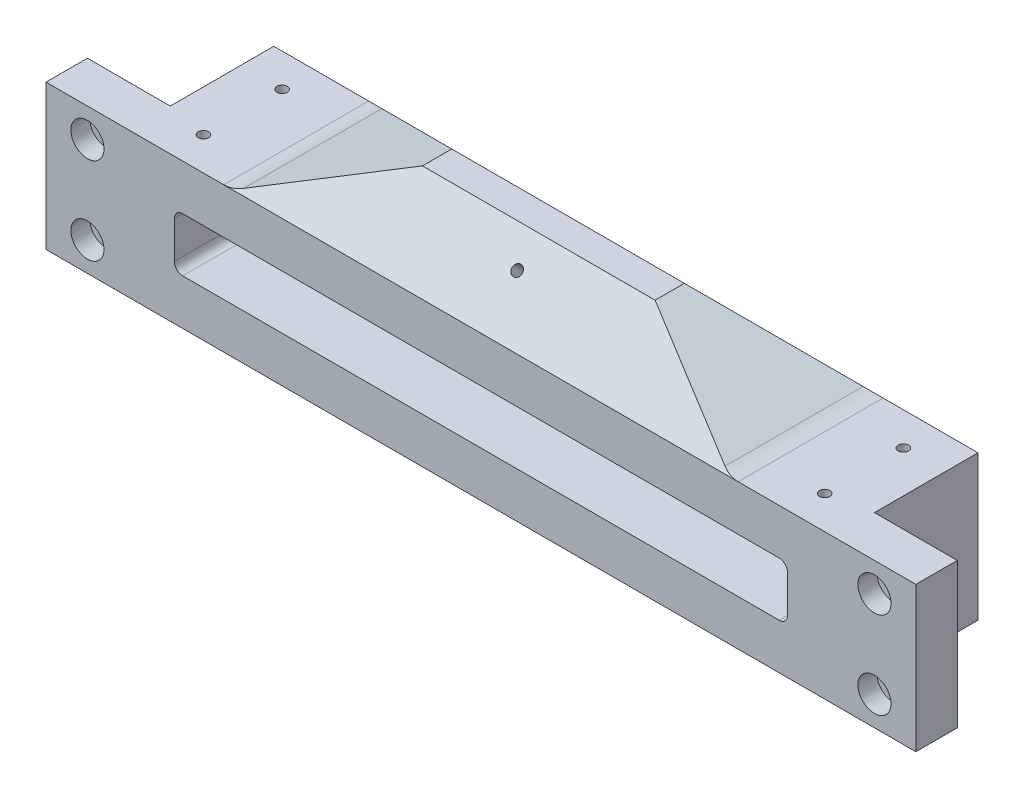
SolidWorks part; units mm, degrees
material "AISI Type 316L stainless steel"
ref_plane "Front Plane" through (0, 0, 0) normal (0, 0, 1) x (1, 0, 0)
ref_plane "Top Plane" through (0, 0, 0) normal (0, 1, 0) x (1, 0, 0)
ref_plane "Right Plane" through (0, 0, 0) normal (1, 0, 0) x (0, 0, -1)
sketch "Sketch1" plane through (0, 0, 0) normal (0, 0, 1) x (1, 0, 0)
  line L1 (80, -12.5) -> (-80, -12.5)
  line L2 (80, -12.5) -> (80, 12.5)
  line L3 (80, 12.5) -> (-80, 12.5)
  line L4 (-80, -12.5) -> (-80, 12.5)
  line L5 (80, -12.5) -> (-80, 12.5) construction
  line L6 (80, 12.5) -> (-80, -12.5) construction
  dimension "D1" = 25
  dimension "D2" = 160
sketch "Sketch2" plane through (0, 0, 0) normal (1, 0, 0) x (0, 0, -1)
  line L0 (17.5, 0) -> (-8.75, 26.25)
  line L1 (0, -12.5) -> (0, 12.5) construction
  line L2 (-17.5, 17.5) -> (0, 35)
  line L3 (0, 12.5) -> (0, -12.5) construction
  line L4 (19.25, 0) -> (-19.25, 0) construction
  line L5 (0, 28.875) -> (0, -28.875) construction
  line L6 (17.5, 17.5) -> (0, 35)
  line L7 (-17.5, 17.5) -> (-17.5, -17.5)
  line L8 (-17.5, -17.5) -> (17.5, -17.5)
  line L9 (17.5, -17.5) -> (17.5, 17.5)
  point P13 (0, 12.5)
  point P19 (0, -12.5)
  dimension "D1" = 45
  dimension "D2" = 5
  dimension "D3" = 5
sketch "Sketch3" plane through (0, 0, 0) normal (0, 0, 1) x (1, 0, 0)
  line L0 (80, -12.5) -> (-80, 12.5) construction
  line L1 (85, -17.5) -> (-85, -17.5)
  line L2 (85, -17.5) -> (85, 17.5)
  line L3 (85, 17.5) -> (-85, 17.5)
  line L4 (-85, -17.5) -> (-85, 17.5)
  line L5 (85, -17.5) -> (-85, 17.5) construction
  line L6 (85, 17.5) -> (-85, -17.5) construction
  line L7 (80, -12.5) -> (-80, -12.5) construction
  line L8 (-80, -12.5) -> (-80, 12.5) construction
  point P0 (0, 0)
  dimension "D1" = 5
  dimension "D2" = 5
extrude "Boss-Extrude1" add sketch "Sketch2" along normal up to vertex (85 mm away) from vertex at -85 contours L8 L9 L0 L2 L7 | L0 L9 L6 L2 starting at point (-85, -17.5, 0)
extrude "Cut-Extrude2" cut sketch "Sketch1" along normal blind 3 from surface at -17.5 starting at face at (0, 0, -17.5)
sketch "Sketch7" plane through (0, 0, -14.5) normal (0, 0, -1) x (-1, 0, 0)
  line L0 (-80, -12.5) -> (-80, 12.5) construction
  line L1 (74, -6.5) -> (-74, -6.5)
  line L2 (74, -6.5) -> (74, 6.5)
  line L3 (74, 6.5) -> (-74, 6.5)
  line L4 (-74, -6.5) -> (-74, 6.5)
  line L5 (74, -6.5) -> (-74, 6.5) construction
  line L6 (74, 6.5) -> (-74, -6.5) construction
  line L7 (-80, 12.5) -> (80, 12.5) construction
  point P0 (0, 0)
  dimension "D1" = 6
  dimension "D2" = 6
extrude "Cut-Extrude4" cut sketch "Sketch7" against normal through all both
sketch "Sketch8" plane through (0, 0, -14.5) normal (0, 0, -1) x (-1, 0, 0)
  line L0 (-74, 6.5) -> (-80, 12.5) construction
  line L1 (77, -9.5) -> (-77, -9.5)
  line L2 (77, -9.5) -> (77, 9.5)
  line L3 (77, 9.5) -> (-77, 9.5)
  line L4 (-77, -9.5) -> (-77, 9.5)
  line L5 (77, -9.5) -> (-77, 9.5) construction
  line L6 (77, 9.5) -> (-77, -9.5) construction
  line L7 (-77, 9.5) -> (0, 9.5)
  point P0 (0, 0)
  point P10 (-38.5, 9.5)
  point P11 (0, 9.5)
  point P12 (-77, 9.5)
sketch "Sketch15" plane through (0, 17.5, 17.5) normal (0, -0.7071, -0.7071) x (1, 0, 0)
  line L0 (-85, 0) -> (85, -24.7487) construction
  line L1 (85, -24.7487) -> (-85, -24.7487) construction
  point P0 (0, -12.3744)
sketch "Sketch5" plane through (0, 0, -17.5) normal (0, 0, -1) x (-1, 0, 0)
  line L0 (-85, 17.5) -> (-60, 17.5)
  line L1 (-85, 17.5) -> (85, 17.5) construction
  line L2 (-60, 17.5) -> (-20, 35)
  line L3 (-85, 35) -> (85, 35) construction
  line L4 (-20, 35) -> (-85, 35)
  line L5 (-85, 35) -> (-85, 17.5)
  dimension "D1" = 25
  dimension "D2" = 65
extrude "Cut-Extrude3" cut sketch "Sketch5" against normal through all both
mirror "Mirror1" about plane through (0, 0, 0) normal (1, 0, 0) of "Cut-Extrude3"
fillet "Fillet1" radius 3 4 edges at (80, 12.5, -16) (80, -12.5, -16) (-80, -12.5, -16) (-80, 12.5, -16)
fillet "Fillet2" radius 10 2 edges at (-60, 17.5, 0) (60, 17.5, 0)
hole_wizard "Tap Drill for M2 Tap1" positions "Sketch9" profile "Sketch11" hole size "M2" standard "GB"
sketch "Sketch9" plane through (0, 0, -14.5) normal (0, 0, -1) x (-1, 0, 0)
  line L0 (-77, -9.5) -> (-77, 9.5) construction
  point P0 (-77, 9.5)
  point P3 (-38.5, 9.5)
  point P6 (0, 9.5)
  point P9 (-77, 0)
sketch "Sketch11" plane through (77, 9.5, -14.5) normal (1, 0, 0) x (0, 1, 0)
  line L0 (0, 0) -> (0, 5.4807)
  line L1 (0, 5.4807) -> (0.8, 5)
  line L2 (0.8, 5) -> (0.8, 0)
  line L5 (0.8, 0) -> (0, 0)
  line L10 (0, 5.4807) -> (-0.8, 5) construction
  line L11 (0, -6.35) -> (0, 107.95) construction
  dimension "Hole Dia." = 1.6
  dimension "Hole Depth" = 5
  dimension "Drill Angle" = 118
mirror "Mirror3" about plane through (0, 0, 0) normal (1, 0, 0) of "Tap Drill for M2 Tap1" second plane through (0, 0, 0) second plane normal (0, 1, 0)
hole_wizard "M3 Tapped Hole1" positions "Sketch13" profile "Sketch14" tap size "M3" standard "GB"
sketch "Sketch13" plane through (0, 17.5, 0) normal (0, 1, 0) x (1, 0, 0)
  line L0 (-75, 17.5) -> (-75, -17.5) construction
  line L4 (-28.875, 0) -> (28.875, 0) construction
  line L5 (-85, -17.5) -> (-85, 17.5) construction
  line L8 (-85, 17.5) -> (-62.0918, 17.5) construction
  line L9 (-85, -17.5) -> (-62.0918, -17.5) construction
  point P0 (-75, 9.5)
  point P20 (-75, -9.5)
  dimension "D1" = 8
  dimension "D2" = 10
sketch "Sketch14" plane through (-75, 17.5, -9.5) normal (1, 0, 0) x (0, 0, 1)
  line L0 (0, 0) -> (0, 8.7511)
  line L1 (0, 8.7511) -> (1.25, 8)
  line L2 (1.25, 8) -> (1.25, 0)
  line L5 (1.25, 0) -> (0, 0)
  line L10 (0, 8.7511) -> (-1.25, 8) construction
  line L11 (0, -6.35) -> (0, 107.95) construction
  dimension "Tap Drill Dia." = 2.5
  dimension "Tap Drill Depth" = 8
  dimension "Drill Angle" = 118
mirror "Mirror4" about plane through (0, 0, 0) normal (0, 1, 0) of "M3 Tapped Hole1"
chamfer "Chamfer1" distance 5 1 edges at (0, 35, 0)
fillet "Fillet3" radius 2 4 edges at (-74, -6.5, 1.5) (74, -6.5, 1.5) (74, 6.5, 1.5) (-74, 6.5, 1.5)
hole_wizard "Tap Drill for M3 Tap4" positions "Sketch18" profile "Sketch19" hole size "M3" standard "GB"
sketch "Sketch18" plane through (0, 17.5, 17.5) normal (0, 0.7071, 0.7071) x (1, 0, 0)
  line L0 (-85, 0) -> (85, 24.7487) construction
  point P0 (0, 12.3744)
sketch "Sketch19" plane through (0, 26.25, 8.75) normal (1, 0, 0) x (0, -0.7071, 0.7071)
  line L0 (0, 0) -> (0, 5.7511)
  line L1 (0, 5.7511) -> (1.25, 5)
  line L2 (1.25, 5) -> (1.25, 0)
  line L5 (1.25, 0) -> (0, 0)
  line L10 (0, 5.7511) -> (-1.25, 5) construction
  line L11 (0, -6.35) -> (0, 107.95) construction
  dimension "Hole Dia." = 2.5
  dimension "Hole Depth" = 5
  dimension "Drill Angle" = 118
sketch "Sketch20" plane through (0, 0, 17.5) normal (0, 0, -1) x (-1, 0, 0)
  line L0 (-85, 17.5) -> (-62.0918, 17.5) construction
  line L1 (-85, 17.5) -> (-105, 17.5)
  line L2 (-85, 17.5) -> (-85, -17.5)
  line L3 (-85, -17.5) -> (-105, -17.5)
  line L4 (-105, 17.5) -> (-105, -17.5)
  line L5 (-85, -17.5) -> (85, -17.5) construction
  line L9 (-85, -17.5) -> (-85, 17.5) construction
  dimension "D1" = 20
extrude "Boss-Extrude2" add sketch "Sketch20" along normal blind 10
sketch "Sketch21" plane through (0, 0, 17.5) normal (0, 0, -1) x (-1, 0, 0)
  line L0 (-95, -17.5) -> (-95, 17.5) construction
  line L1 (-105, -17.5) -> (-85, -17.5) construction
  line L2 (-85, 17.5) -> (-105, 17.5) construction
  point P0 (-95, -10.5)
  point P1 (-95, 10.5)
  dimension "D1" = 7
  dimension "D2" = 7
hole_wizard "CBORE for M4 Hexagon socket head cap screws1" positions "Sketch22" profile "Sketch24" counterbore size "M4" standard "GB"
sketch "Sketch22" plane through (0, 0, 17.5) normal (0, 0, 1) x (1, 0, 0)
  point P0 (95, 10.5)
  point P3 (95, -10.5)
sketch "Sketch24" plane through (95, 10.5, 17.5) normal (1, 0, 0) x (0, -1, 0)
  line L0 (0, 0) -> (0, 35)
  line L1 (0, 35) -> (2.25, 35)
  line L3 (2.25, 35) -> (2.25, 4.6)
  line L4 (2.25, 4.6) -> (4, 4.6)
  line L5 (4, 4.6) -> (4, 0)
  line L7 (4, 0) -> (0, 0)
  line L11 (0, -6.35) -> (0, 107.95) construction
  dimension "Thru Hole Dia." = 4.5
  dimension "Thru Hole Depth" = 35
  dimension "C'Bore Dia." = 8
  dimension "C'Bore Depth" = 4.6
mirror "Mirror5" about plane through (0, 0, 0) normal (1, 0, 0) of "CBORE for M4 Hexagon socket head cap screws1", "Boss-Extrude2"
